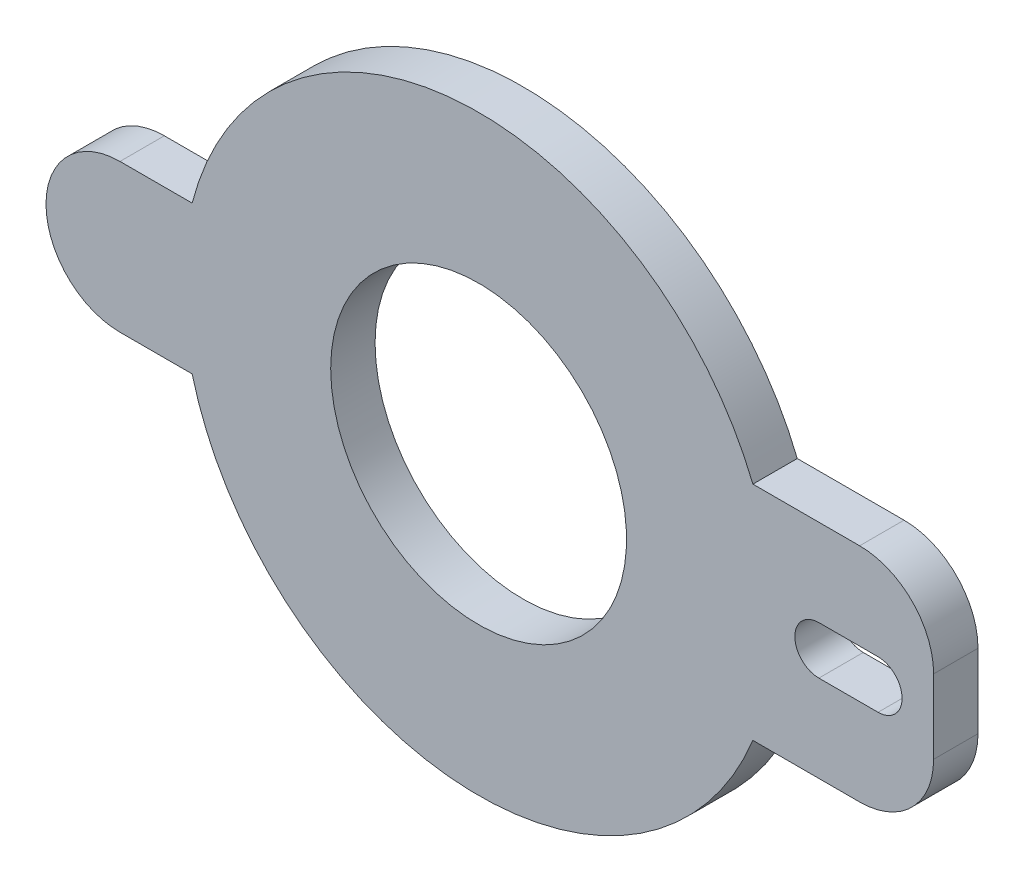
SolidWorks part; units mm, degrees
ref_plane "Front Plane" through (0, 0, 0) normal (0, 0, 1) x (1, 0, 0)
ref_plane "Top Plane" through (0, 0, 0) normal (0, 1, 0) x (1, 0, 0)
ref_plane "Right Plane" through (0, 0, 0) normal (1, 0, 0) x (0, 0, -1)
ref_plane "Plane1" through (0, 0, 6) normal (0, 0, 1) x (1, 0, 0)
sketch "Sketch1" plane through (0, 0, 6) normal (0, 0, 1) x (1, 0, 0)
  line L0 (-91.7618, 17.7034) -> (-101.5189, 17.7034)
  line L1 (-101.5189, -2.2966) -> (-91.7618, -2.2966)
  line L2 (-15.951, -7.2966) -> (-1.5189, -7.2966)
  line L3 (8.4811, 2.7034) -> (8.4811, 12.7034)
  line L4 (-1.5189, 22.7034) -> (-15.951, 22.7034)
  line L5 (-101.5189, 7.7034) -> (18.2194, 7.7034) construction
  line L6 (-7.032, 7.7034) -> (0.968, 7.7034) construction
  line L7 (-7.032, 10.9534) -> (0.968, 10.9534)
  line L8 (-7.032, 4.4534) -> (0.968, 4.4534)
  circle A0 centre (-53.032, 7.7034) radius 20
  arc A1 (-15.951, 22.7034) -> (-91.7618, 17.7034) centre (-53.032, 7.7034) ccw
  arc A2 (-101.5189, 17.7034) -> (-101.5189, -2.2966) centre (-101.5189, 7.7034) ccw
  arc A3 (-91.7618, -2.2966) -> (-15.951, -7.2966) centre (-53.032, 7.7034) ccw
  arc A4 (-1.5189, -7.2966) -> (8.4811, 2.7034) centre (-1.5189, 2.7034) ccw
  arc A5 (8.4811, 12.7034) -> (-1.5189, 22.7034) centre (-1.5189, 12.7034) ccw
  arc A6 (-7.032, 10.9534) -> (-7.032, 4.4534) centre (-7.032, 7.7034) ccw
  arc A7 (0.968, 4.4534) -> (0.968, 10.9534) centre (0.968, 7.7034) ccw
  point P17 (-3.032, 7.7034)
  dimension "D2" = 50
  dimension "D4" = 40
  dimension "D5" = 40
  dimension "D7" = 10
  dimension "D1" = 6.5
  dimension "D3" = 30
  dimension "D6" = 20
  dimension "D8" = 8
extrude "Boss-Extrude1" add sketch "Sketch1" against normal blind 6
